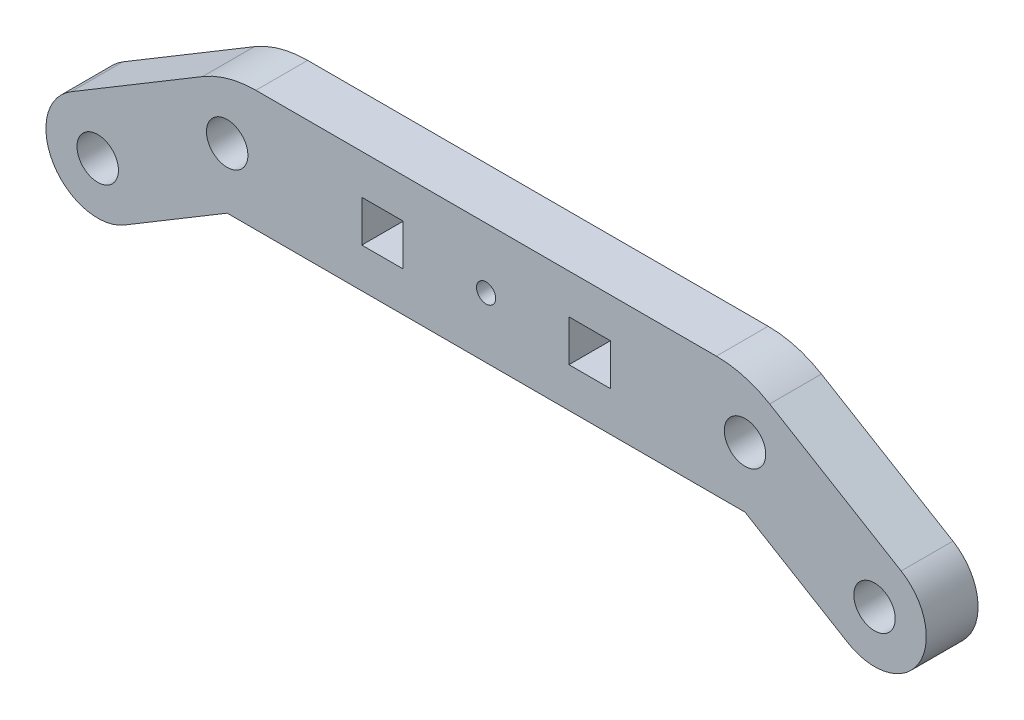
SolidWorks part; units mm, degrees
material "ABS"
ref_plane "Plano frontal" through (0, 0, 0) normal (0, 0, 1) x (1, 0, 0)
ref_plane "Plano superior" through (0, 0, 0) normal (0, 1, 0) x (1, 0, 0)
ref_plane "Plano direito" through (0, 0, 0) normal (1, 0, 0) x (0, 0, -1)
sketch "Esboço1" plane through (0, 0, 0) normal (0, 0, 1) x (1, 0, 0)
  line L0 (0, 0) -> (0, -23.3238) construction
  line L1 (-24, -15.6619) -> (-16, -7.6619) construction
  line L2 (24, -7.6619) -> (16, -7.6619)
  line L3 (80.145, -18.087) -> (50, 0)
  line L4 (24, -7.6619) -> (24, -15.6619)
  line L5 (-50, -23.3238) -> (50, -23.3238)
  line L6 (24, -15.6619) -> (16, -15.6619)
  line L7 (16, -7.6619) -> (16, -15.6619)
  line L8 (24, -7.6619) -> (16, -15.6619) construction
  line L9 (24, -15.6619) -> (16, -7.6619) construction
  line L10 (-24, -7.6619) -> (-16, -15.6619) construction
  line L11 (-16, -7.6619) -> (-16, -15.6619)
  line L12 (-24, -15.6619) -> (-16, -15.6619)
  line L13 (-24, -7.6619) -> (-24, -15.6619)
  line L14 (-24, -7.6619) -> (-16, -7.6619)
  line L15 (50, 0) -> (0, 0)
  line L16 (0, 0) -> (-50, 0)
  line L17 (-50, 0) -> (-80.145, -18.087)
  line L18 (-69.855, -35.2368) -> (-50, -23.3238)
  line L19 (-50, -11.6619) -> (-75, -26.6619) construction
  line L20 (50, -23.3238) -> (69.855, -35.2368)
  line L21 (50, -11.6619) -> (75, -26.6619) construction
  circle A0 centre (-50, -11.6619) radius 4
  circle A1 centre (50, -11.6619) radius 4
  circle A2 centre (0, -11.6619) radius 1.85
  arc A4 (-80.145, -18.087) -> (-69.855, -35.2368) centre (-75, -26.6619) ccw
  arc A5 (80.145, -18.087) -> (69.855, -35.2368) centre (75, -26.6619) cw
  circle A6 centre (-75, -26.6619) radius 4
  circle A7 centre (75, -26.6619) radius 4
  point P0 (0, 0)
  point P1 (20, -11.6619)
  point P13 (63, -13)
  point P24 (-20, -11.6619)
  point P33 (-50, 0)
  point P34 (-55.342, 0)
  point P35 (0, -11.6619)
  dimension "D3" = 8
  dimension "D4" = 100
  dimension "D2" = 10
  dimension "D12" = 8
  dimension "D7" = 40
  dimension "D9" = 3.7
  dimension "D5" = 15
  dimension "D6" = 8
  dimension "D13" = 150
extrude "Ressalto-extrusão1" add sketch "Esboço1" along normal blind 10
fillet "Filete1" radius 20 2 edges at (50, 0, 5) (-50, 0, 5)
